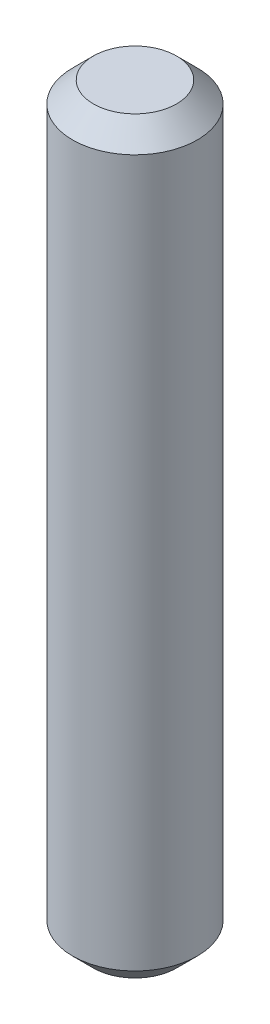
SolidWorks part; units mm, degrees
ref_plane "Спереди" through (0, 0, 0) normal (0, 0, 1) x (1, 0, 0)
ref_plane "Сверху" through (0, 0, 0) normal (0, 1, 0) x (1, 0, 0)
ref_plane "Справа" through (0, 0, 0) normal (1, 0, 0) x (0, 0, -1)
sketch "Эскиз2" plane through (0, 0, 0) normal (0, 1, 0) x (1, 0, 0)
  circle A0 centre (0, 0) radius 1.5
  dimension "D1" = 3
extrude "Бобышка-Вытянуть1" add sketch "Эскиз2" along normal blind 18
chamfer "Фаска1" distance 0.5 angle 45 2 edges at (0, 0, 1.5) (0, 18, 1.5)
